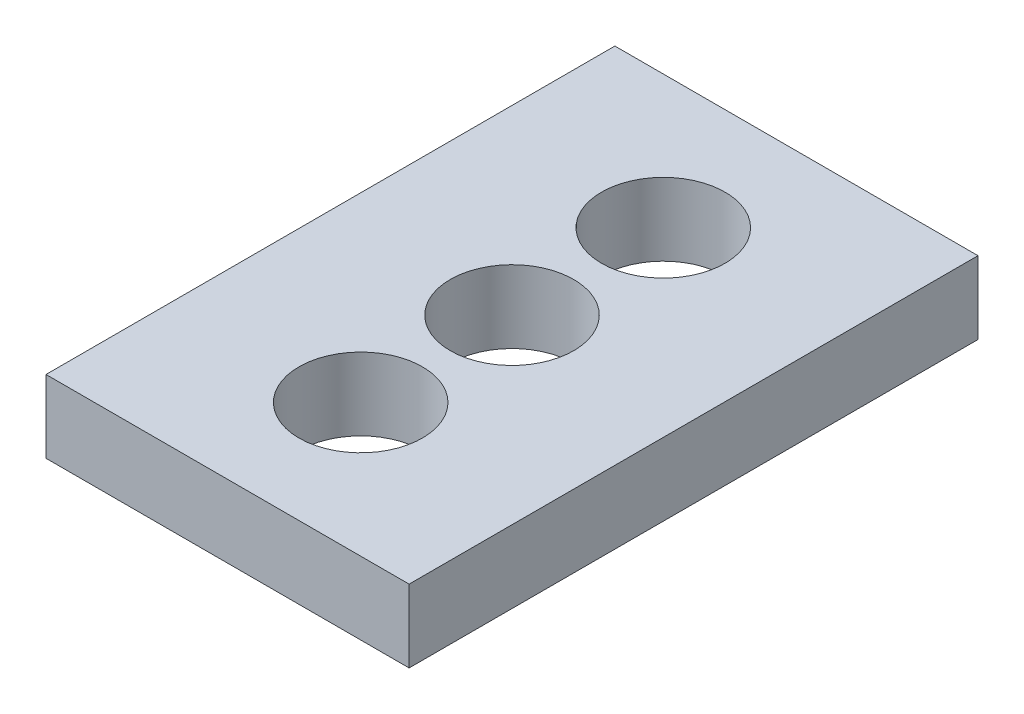
SolidWorks part; units mm, degrees
ref_plane "Front Plane" through (0, 0, 0) normal (0, 0, 1) x (1, 0, 0)
ref_plane "Top Plane" through (0, 0, 0) normal (0, 1, 0) x (1, 0, 0)
ref_plane "Right Plane" through (0, 0, 0) normal (1, 0, 0) x (0, 0, -1)
sketch "Esboço1" plane through (0, 0, 0) normal (0, 1, 0) x (1, 0, 0)
  line L0 (-55.5969, -15.6454) -> (-40.5969, -15.6454)
  line L1 (-55.5969, -15.6454) -> (-55.5969, 7.8546)
  line L2 (-55.5969, 7.8546) -> (-40.5969, 7.8546)
  line L3 (-40.5969, -15.6454) -> (-40.5969, 7.8546)
  line L4 (-55.5969, -15.6454) -> (-40.5969, 7.8546) construction
  line L5 (-55.5969, 7.8546) -> (-40.5969, -15.6454) construction
  circle A3 centre (-48.0969, 2.3546) radius 2.55
  circle A4 centre (-48.0969, -3.8954) radius 2.55
  circle A5 centre (-48.0969, -10.1454) radius 2.55
  point P0 (-48.0969, -3.8954)
  dimension "D1" = 7.5
  dimension "D4" = 6.25
  dimension "D5" = 6.25
  dimension "D6" = 23.5
  dimension "D7" = 5.5
extrude "Ressalto-extrusão1" add sketch "Esboço1" along normal blind 3
